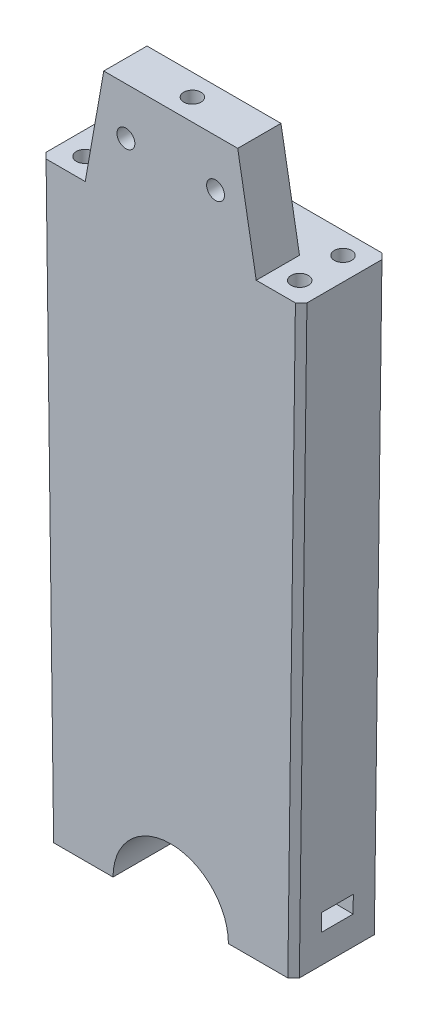
SolidWorks part; units mm, degrees
ref_plane "前视基准面" through (0, 0, 0) normal (0, 0, 1) x (1, 0, 0)
ref_plane "上视基准面" through (0, 0, 0) normal (0, 1, 0) x (1, 0, 0)
ref_plane "右视基准面" through (0, 0, 0) normal (1, 0, 0) x (0, 0, -1)
sketch "草图1" plane through (0, 0, 0) normal (0, 0, 1) x (1, 0, 0)
  line L0 (-10.835, -18.4) -> (-9.5212, -120.4)
  line L1 (26.795, -18.4) -> (34.385, -18.4)
  line L2 (34.385, -18.4) -> (33.0712, -120.4)
  line L3 (-3.245, -18.4) -> (-3.045, -18.4)
  line L5 (1.775, -120.4) -> (-9.5212, -120.4)
  line L6 (-3.245, -18.4) -> (-10.835, -18.4)
  line L7 (0.1647, -0.2) -> (-3.045, -18.4)
  line L8 (21.775, -120.4) -> (33.0712, -120.4)
  line L13 (0.1647, -0.2) -> (23.3853, -0.2)
  line L14 (26.795, -18.4) -> (26.595, -18.4)
  line L15 (23.3853, -0.2) -> (26.595, -18.4)
  circle A1 centre (4.005, -8.4) radius 1.55
  circle A2 centre (19.545, -8.4) radius 1.55
  arc A3 (21.775, -120.4) -> (1.775, -120.4) centre (11.775, -120.4) ccw
extrude "凸台-拉伸1" add sketch "草图1" along normal blind 15
sketch "草图2" plane through (0, -0.2, 0) normal (0, 1, 0) x (1, 0, 0)
  line L0 (23.3853, -7.5) -> (-22.2386, -7.5)
  line L1 (23.3853, -15) -> (23.3853, 0) construction
  line L2 (-22.2386, -7.5) -> (-22.2386, 0)
  line L3 (-22.2386, 0) -> (39.199, 0)
  line L4 (39.199, 0) -> (39.199, -7.5)
  line L5 (39.199, -7.5) -> (23.3853, -7.5)
extrude "切除-拉伸1" cut sketch "草图2" against normal blind 18.2
sketch "草图3" plane through (0, -0.2, 0) normal (0, 1, 0) x (1, 0, 0)
  circle A0 centre (11.775, -11.25) radius 1.5
extrude "切除-拉伸2" cut sketch "草图3" against normal blind 12
sketch "草图4" plane through (0, -18.4, 0) normal (0, 1, 0) x (1, 0, 0)
  circle A0 centre (30.385, -3.75) radius 1.5
  circle A1 centre (30.385, -11.25) radius 1.5
  circle A2 centre (-6.835, -11.25) radius 1.5
  circle A3 centre (-6.835, -3.75) radius 1.5
extrude "切除-拉伸3" cut sketch "草图4" against normal blind 12
chamfer "倒角1" distance 1 angle 45 4 edges at (-10.1781, -69.4, 15) (-10.1781, -69.4, 0) (33.7281, -69.4, 15) (33.7281, -69.4, 0)
sketch "草图5" plane through (34.6162, -0.4459, 0) normal (0.9999, -0.0129, 0) x (0, 0, -1)
  line L2 (-7.5, -114.9641) -> (-4.75, -114.9641)
  line L3 (-7.5, -114.9641) -> (-10.25, -114.9641)
  line L4 (-4.75, -114.9641) -> (-4.75, -111.9641)
  line L5 (-10.25, -114.9641) -> (-10.25, -111.9641)
  line L6 (-10.25, -111.9641) -> (-4.75, -111.9641)
extrude "切除-拉伸4" cut sketch "草图5" against normal blind 9.5
sketch "草图6" plane through (-11.0702, -0.1426, 0) normal (-0.9999, -0.0129, 0) x (0, 0, 1)
  line L2 (7.5, -115.2674) -> (4.75, -115.2674)
  line L3 (7.5, -115.2674) -> (10.25, -115.2674)
  line L4 (4.75, -115.2674) -> (4.75, -112.2674)
  line L5 (4.75, -112.2674) -> (10.25, -112.2674)
  line L6 (10.25, -112.2674) -> (10.25, -115.2674)
extrude "切除-拉伸5" cut sketch "草图6" against normal blind 9.5
sketch "草图7" plane through (0, -120.4, 0) normal (0, -1, 0) x (1, 0, 0)
  circle A0 centre (27.425, 7.5) radius 1.45
  circle A1 centre (-3.875, 7.5) radius 1.45
extrude "切除-拉伸6" cut sketch "草图7" against normal blind 20
